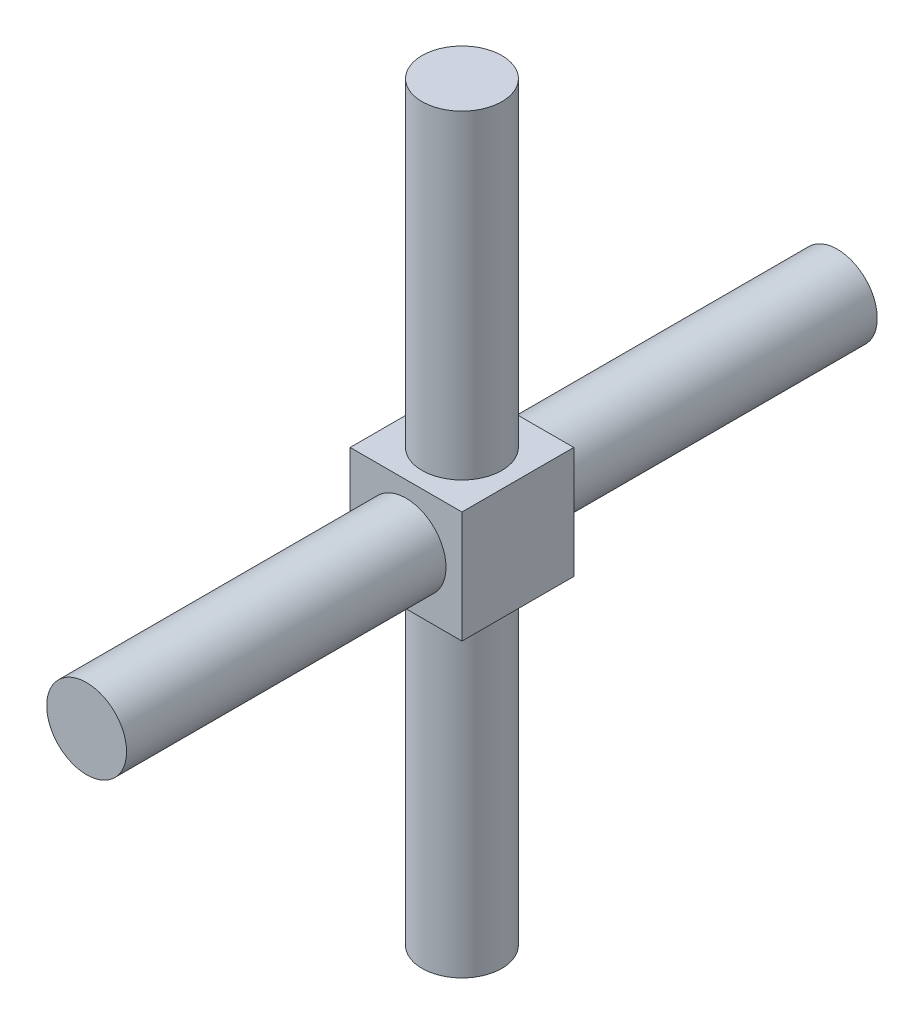
SolidWorks part; units mm, degrees
ref_plane "정면" through (0, 0, 0) normal (0, 0, 1) x (1, 0, 0)
ref_plane "윗면" through (0, 0, 0) normal (0, 1, 0) x (1, 0, 0)
ref_plane "우측면" through (0, 0, 0) normal (1, 0, 0) x (0, 0, -1)
sketch "스케치1" plane through (0, 0, 0) normal (0, 0, 1) x (1, 0, 0)
  line L1 (35, -35) -> (-35, -35)
  line L2 (35, -35) -> (35, 35)
  line L3 (35, 35) -> (-35, 35)
  line L4 (-35, -35) -> (-35, 35)
  line L5 (35, -35) -> (-35, 35) construction
  line L6 (35, 35) -> (-35, -35) construction
  point P0 (0, 0)
  dimension "D1" = 70
  dimension "D2" = 70
extrude "보스-돌출1" add sketch "스케치1" along normal blind 70
sketch "스케치4" plane through (0, 0, 70) normal (0, 0, 1) x (1, 0, 0)
  circle A0 centre (0, 0) radius 25
  dimension "D1" = 50
extrude "보스-돌출2" add sketch "스케치4" along normal blind 200
ref_plane "평면1" through (0, 0, 35) normal (0, 0, 1) x (1, 0, 0)
mirror "대칭 복사1" about plane through (0, 0, 35) normal (0, 0, 1) of "보스-돌출2"
sketch "스케치5" plane through (0, 35, 0) normal (0, 1, 0) x (1, 0, 0)
  line L0 (-38.5, -35) -> (38.5, -35) construction
  line L1 (0, -38.5) -> (0, 38.5) construction
  line L2 (35, -70) -> (35, 0) construction
  circle A0 centre (0, -35) radius 25
  point P10 (35, -35)
  dimension "D1" = 50
extrude "보스-돌출3" add sketch "스케치5" along normal blind 200
mirror "대칭 복사2" about plane through (0, 0, 0) normal (0, 1, 0) of "보스-돌출3"
